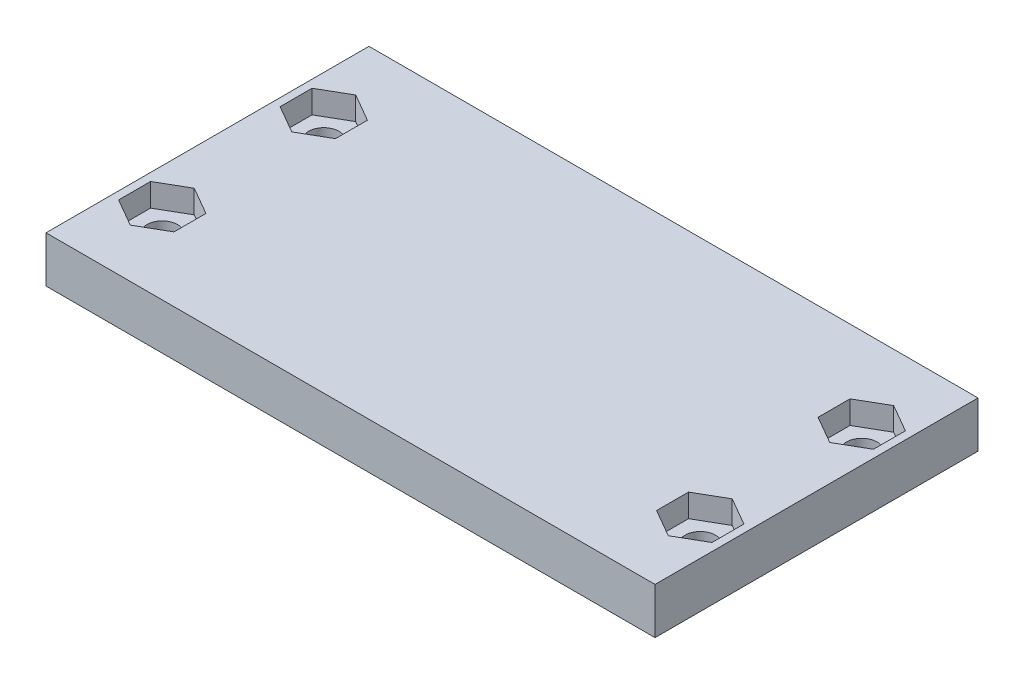
SolidWorks part; units mm, degrees
ref_plane "Front Plane" through (0, 0, 0) normal (0, 0, 1) x (1, 0, 0)
ref_plane "Top Plane" through (0, 0, 0) normal (0, 1, 0) x (1, 0, 0)
ref_plane "Right Plane" through (0, 0, 0) normal (1, 0, 0) x (0, 0, -1)
sketch "Sketch1" plane through (0, 0, 0) normal (0, 1, 0) x (1, 0, 0)
  line L1 (0, 0) -> (66, 0)
  line L2 (0, 0) -> (0, 35)
  line L3 (0, 35) -> (66, 35)
  line L4 (66, 0) -> (66, 35)
  dimension "D1" = 66
  dimension "D2" = 35
extrude "Boss-Extrude1" add sketch "Sketch1" along normal blind 5
sketch "Sketch2" plane through (0, 5, 0) normal (0, 1, 0) x (1, 0, 0)
  line L0 (0, 17.5) -> (3.85, 17.5) construction
  line L1 (65.15, 7.0179) -> (62.15, 5.2859)
  line L2 (0, 35) -> (0, 0) construction
  line L3 (33, 35) -> (33, 0) construction
  line L4 (66, 35) -> (0, 35) construction
  line L5 (0, 0) -> (66, 0) construction
  line L6 (3.85, 35) -> (3.85, 26.25) construction
  line L7 (3.85, 0) -> (3.85, 8.75) construction
  line L8 (65.15, 10.4821) -> (65.15, 7.0179)
  line L9 (3.85, 29.7141) -> (0.85, 27.9821)
  line L10 (0.85, 27.9821) -> (0.85, 24.5179)
  line L11 (0.85, 24.5179) -> (3.85, 22.7859)
  line L12 (3.85, 22.7859) -> (6.85, 24.5179)
  line L13 (6.85, 24.5179) -> (6.85, 27.9821)
  line L14 (6.85, 27.9821) -> (3.85, 29.7141)
  line L15 (3.85, 5.2859) -> (6.85, 7.0179)
  line L16 (6.85, 7.0179) -> (6.85, 10.4821)
  line L17 (6.85, 10.4821) -> (3.85, 12.2141)
  line L18 (3.85, 12.2141) -> (0.85, 10.4821)
  line L19 (0.85, 10.4821) -> (0.85, 7.0179)
  line L20 (0.85, 7.0179) -> (3.85, 5.2859)
  line L21 (62.15, 12.2141) -> (65.15, 10.4821)
  line L22 (59.15, 10.4821) -> (62.15, 12.2141)
  line L23 (59.15, 7.0179) -> (59.15, 10.4821)
  line L24 (62.15, 5.2859) -> (59.15, 7.0179)
  line L25 (59.15, 27.9821) -> (62.15, 29.7141)
  line L26 (59.15, 24.5179) -> (59.15, 27.9821)
  line L27 (62.15, 22.7859) -> (59.15, 24.5179)
  line L28 (65.15, 24.5179) -> (62.15, 22.7859)
  line L29 (65.15, 27.9821) -> (65.15, 24.5179)
  line L30 (62.15, 29.7141) -> (65.15, 27.9821)
  circle A0 centre (3.85, 26.25) radius 3 construction
  circle A1 centre (3.85, 8.75) radius 3 construction
  dimension "D2" = 6
  dimension "D1" = 8.75
  dimension "D3" = 3.85
  dimension "D4" = 8.75
extrude "Cut-Extrude1" cut sketch "Sketch2" against normal blind 2.5
sketch "Sketch3" plane through (0, 5, 0) normal (0, 1, 0) x (1, 0, 0)
  line L0 (66, 35) -> (0, 35) construction
  line L1 (0, 0) -> (66, 0) construction
  line L2 (0, 35) -> (0, 0) construction
  line L3 (66, 0) -> (66, 35) construction
  circle A0 centre (3.85, 8.75) radius 1.65
  circle A1 centre (3.85, 26.25) radius 1.65
  circle A2 centre (62.15, 26.25) radius 1.65
  circle A3 centre (62.15, 8.75) radius 1.65
  dimension "D1" = 3.3
  dimension "D2" = 8.75
  dimension "D3" = 8.75
  dimension "D4" = 8.75
  dimension "D5" = 3.85
  dimension "D6" = 3.85
  dimension "D7" = 3.85
  dimension "D8" = 3.85
extrude "Cut-Extrude3" cut sketch "Sketch3" against normal through all
